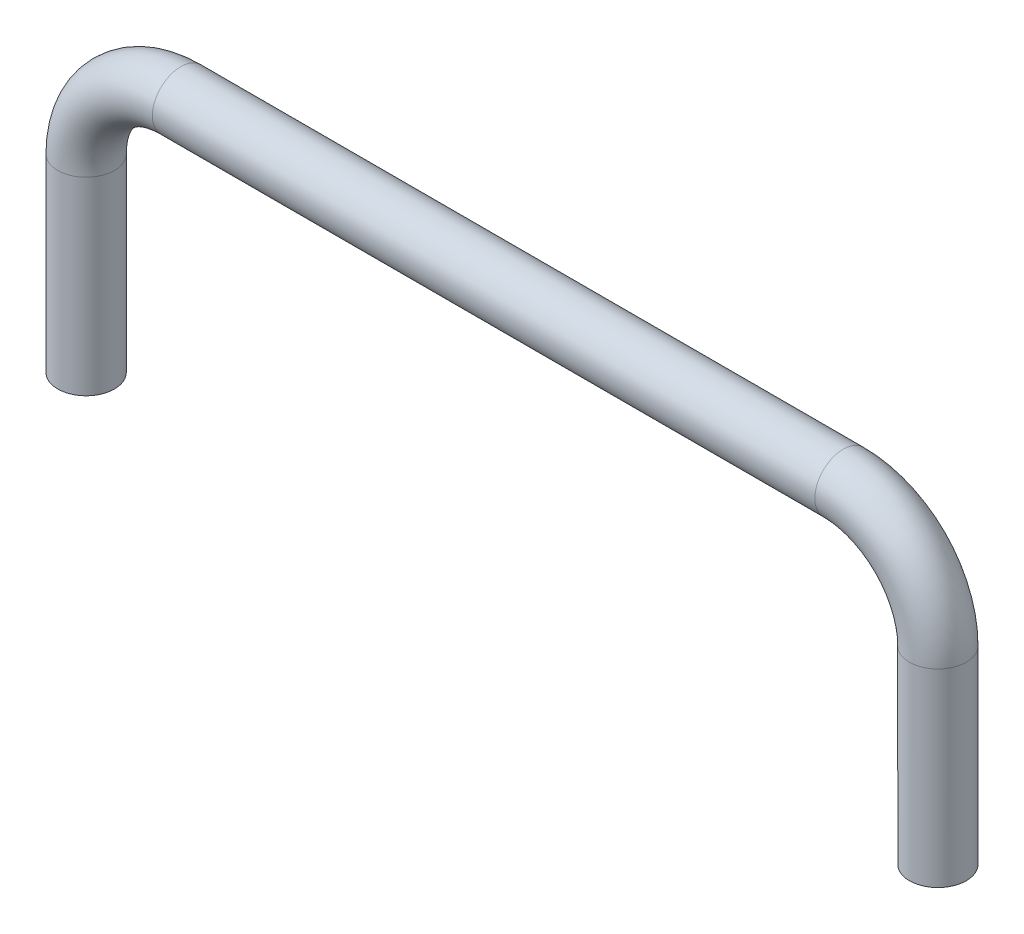
SolidWorks part; units mm, degrees
ref_plane "前视基准面" through (0, 0, 0) normal (0, 0, 1) x (1, 0, 0)
ref_plane "上视基准面" through (0, 0, 0) normal (0, 1, 0) x (1, 0, 0)
ref_plane "右视基准面" through (0, 0, 0) normal (1, 0, 0) x (0, 0, -1)
sketch "草图1" plane through (0, 0, 0) normal (0, 0, 1) x (1, 0, 0)
  line L0 (0, 0) -> (0, 20)
  line L1 (10, 30) -> (80, 30)
  line L2 (90, 20) -> (90, 0)
  arc A0 (90, 20) -> (80, 30) centre (80, 20) ccw
  arc A1 (10, 30) -> (0, 20) centre (10, 20) ccw
  point P7 (90, 30)
  point P10 (0, 30)
  dimension "D4" = 10
  dimension "D1" = 90
  dimension "D2" = 30
  dimension "D3" = 30
sketch "草图2" plane through (0, 0, 0) normal (0, 1, 0) x (1, 0, 0)
  circle A0 centre (0, 0) radius 3
  dimension "D1" = 6
sweep "扫描1" add profiles "草图2" path "草图1"
sketch "草图3" plane through (0, 0, 0) normal (0, -1, 0) x (1, 0, 0)
  circle A0 centre (0, 0) radius 1.6
  circle A1 centre (90, 0) radius 1.6
  dimension "D1" = 3.2
extrude "切除-拉伸1" cut sketch "草图3" against normal blind 10
